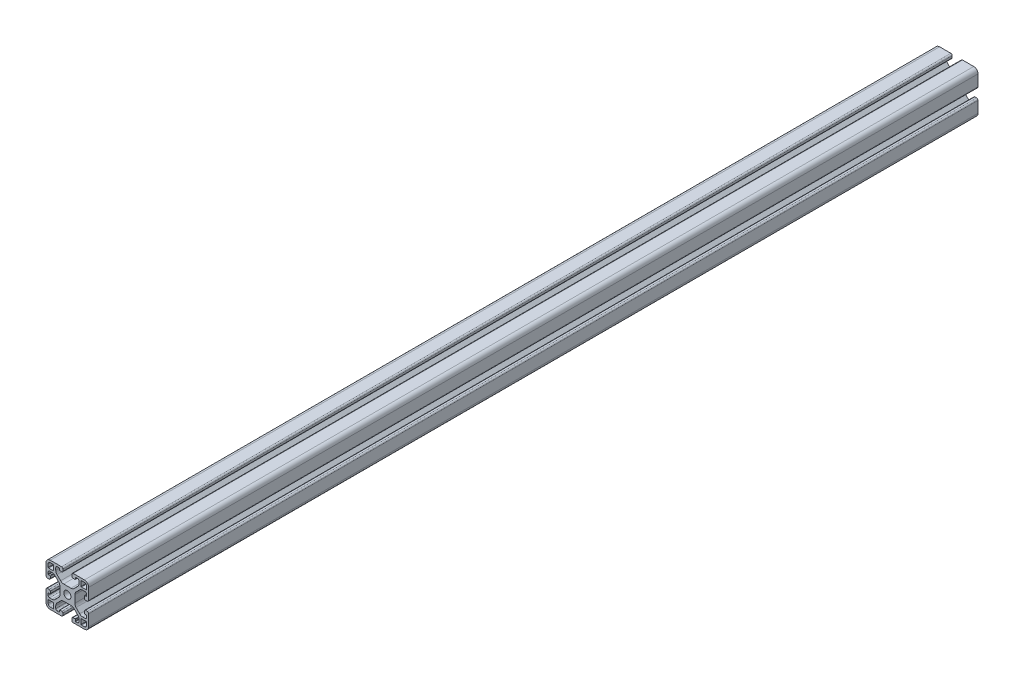
SolidWorks part; units mm, degrees
ref_plane "Plan de face" through (0, 0, 0) normal (0, 0, 1) x (1, 0, 0)
ref_plane "Plan de dessus" through (0, 0, 0) normal (0, 1, 0) x (1, 0, 0)
ref_plane "Plan de droite" through (0, 0, 0) normal (1, 0, 0) x (0, 0, -1)
ref_plane "Plan1" through (0, 0, 20) normal (0, 0, 1) x (1, 0, 0)
sketch "Esquisse1" plane through (0, 0, 20) normal (0, 0, 1) x (1, 0, 0)
  line L0 (20.3, 3) -> (18.9, 3)
  line L1 (18.1, 2.2) -> (18.1, 1)
  line L2 (19.1, 0) -> (27, 0)
  line L3 (30, 3) -> (30, 10.9)
  line L4 (29, 11.9) -> (27.8, 11.9)
  line L5 (27, 11.1) -> (27, 9.7)
  line L6 (27.3, 9.4) -> (28.2, 9.4)
  line L7 (28.5, 9.1) -> (28.5, 7.85)
  line L8 (27.5, 6.85) -> (25.8069, 6.85)
  line L9 (23.6855, 7.7287) -> (21.1287, 10.2855)
  line L10 (20.25, 12.4069) -> (20.25, 17.5931)
  line L11 (21.1287, 19.7145) -> (23.6855, 22.2713)
  line L12 (25.8069, 23.15) -> (27.5, 23.15)
  line L13 (28.5, 22.15) -> (28.5, 20.9)
  line L14 (28.2, 20.6) -> (27.3, 20.6)
  line L15 (27, 20.3) -> (27, 18.9)
  line L16 (27.8, 18.1) -> (29, 18.1)
  line L17 (30, 19.1) -> (30, 27)
  line L18 (27, 30) -> (19.1, 30)
  line L19 (18.1, 29) -> (18.1, 27.8)
  line L20 (18.9, 27) -> (20.3, 27)
  line L21 (20.6, 27.3) -> (20.6, 28.2)
  line L22 (20.9, 28.5) -> (22.15, 28.5)
  line L23 (23.15, 27.5) -> (23.15, 25.8069)
  line L24 (22.2713, 23.6855) -> (19.7145, 21.1287)
  line L25 (17.5931, 20.25) -> (12.4069, 20.25)
  line L26 (10.2855, 21.1287) -> (7.7287, 23.6855)
  line L27 (6.85, 25.8069) -> (6.85, 27.5)
  line L28 (7.85, 28.5) -> (9.1, 28.5)
  line L29 (9.4, 28.2) -> (9.4, 27.3)
  line L30 (9.7, 27) -> (11.1, 27)
  line L31 (11.9, 27.8) -> (11.9, 29)
  line L32 (10.9, 30) -> (3, 30)
  line L33 (0, 27) -> (0, 19.1)
  line L34 (1, 18.1) -> (2.2, 18.1)
  line L35 (3, 18.9) -> (3, 20.3)
  line L36 (2.7, 20.6) -> (1.8, 20.6)
  line L37 (1.5, 20.9) -> (1.5, 22.15)
  line L38 (2.5, 23.15) -> (4.1931, 23.15)
  line L39 (6.3145, 22.2713) -> (8.8713, 19.7145)
  line L40 (9.75, 17.5931) -> (9.75, 12.4069)
  line L41 (8.8713, 10.2855) -> (6.3145, 7.7287)
  line L42 (4.1931, 6.85) -> (2.5, 6.85)
  line L43 (1.5, 7.85) -> (1.5, 9.1)
  line L44 (1.8, 9.4) -> (2.7, 9.4)
  line L45 (3, 9.7) -> (3, 11.1)
  line L46 (2.2, 11.9) -> (1, 11.9)
  line L47 (0, 10.9) -> (0, 3)
  line L48 (3, 0) -> (10.9, 0)
  line L49 (11.9, 1) -> (11.9, 2.2)
  line L50 (11.1, 3) -> (9.7, 3)
  line L51 (9.4, 2.7) -> (9.4, 1.8)
  line L52 (9.1, 1.5) -> (7.85, 1.5)
  line L53 (6.85, 2.5) -> (6.85, 4.1931)
  line L54 (7.7287, 6.3145) -> (10.2855, 8.8713)
  line L55 (12.4069, 9.75) -> (17.5931, 9.75)
  line L56 (19.7145, 8.8713) -> (22.2713, 6.3145)
  line L57 (23.15, 4.1931) -> (23.15, 2.5)
  line L58 (22.15, 1.5) -> (20.9, 1.5)
  line L59 (20.6, 1.8) -> (20.6, 2.7)
  line L60 (5.35, 5.05) -> (5.35, 1.8)
  line L61 (5.05, 1.5) -> (3, 1.5)
  line L62 (1.5, 3) -> (1.5, 5.05)
  line L63 (1.8, 5.35) -> (5.05, 5.35)
  line L64 (24.95, 5.35) -> (28.2, 5.35)
  line L65 (28.5, 5.05) -> (28.5, 3)
  line L66 (27, 1.5) -> (24.95, 1.5)
  line L67 (24.65, 1.8) -> (24.65, 5.05)
  line L68 (24.65, 24.95) -> (24.65, 28.2)
  line L69 (24.95, 28.5) -> (27, 28.5)
  line L70 (28.5, 27) -> (28.5, 24.95)
  line L71 (28.2, 24.65) -> (24.95, 24.65)
  line L72 (5.05, 24.65) -> (1.8, 24.65)
  line L73 (1.5, 24.95) -> (1.5, 27)
  line L74 (3, 28.5) -> (5.05, 28.5)
  line L75 (5.35, 28.2) -> (5.35, 24.95)
  arc A0 (20.6, 2.7) -> (20.3, 3) centre (20.3, 2.7) ccw
  arc A1 (18.9, 3) -> (18.1, 2.2) centre (18.9, 2.2) ccw
  arc A2 (18.1, 1) -> (19.1, 0) centre (19.1, 1) ccw
  arc A3 (27, 0) -> (30, 3) centre (27, 3) ccw
  arc A4 (30, 10.9) -> (29, 11.9) centre (29, 10.9) ccw
  arc A5 (27.8, 11.9) -> (27, 11.1) centre (27.8, 11.1) ccw
  arc A6 (27, 9.7) -> (27.3, 9.4) centre (27.3, 9.7) ccw
  arc A7 (28.2, 9.4) -> (28.5, 9.1) centre (28.2, 9.1) cw
  arc A8 (28.5, 7.85) -> (27.5, 6.85) centre (27.5, 7.85) cw
  arc A9 (25.8069, 6.85) -> (23.6855, 7.7287) centre (25.8069, 9.85) cw
  arc A10 (21.1287, 10.2855) -> (20.25, 12.4069) centre (23.25, 12.4069) cw
  arc A11 (20.25, 17.5931) -> (21.1287, 19.7145) centre (23.25, 17.5931) cw
  arc A12 (23.6855, 22.2713) -> (25.8069, 23.15) centre (25.8069, 20.15) cw
  arc A13 (27.5, 23.15) -> (28.5, 22.15) centre (27.5, 22.15) cw
  arc A14 (28.5, 20.9) -> (28.2, 20.6) centre (28.2, 20.9) cw
  arc A15 (27.3, 20.6) -> (27, 20.3) centre (27.3, 20.3) ccw
  arc A16 (27, 18.9) -> (27.8, 18.1) centre (27.8, 18.9) ccw
  arc A17 (29, 18.1) -> (30, 19.1) centre (29, 19.1) ccw
  arc A18 (30, 27) -> (27, 30) centre (27, 27) ccw
  arc A19 (19.1, 30) -> (18.1, 29) centre (19.1, 29) ccw
  arc A20 (18.1, 27.8) -> (18.9, 27) centre (18.9, 27.8) ccw
  arc A21 (20.3, 27) -> (20.6, 27.3) centre (20.3, 27.3) ccw
  arc A22 (20.6, 28.2) -> (20.9, 28.5) centre (20.9, 28.2) cw
  arc A23 (22.15, 28.5) -> (23.15, 27.5) centre (22.15, 27.5) cw
  arc A24 (23.15, 25.8069) -> (22.2713, 23.6855) centre (20.15, 25.8069) cw
  arc A25 (19.7145, 21.1287) -> (17.5931, 20.25) centre (17.5931, 23.25) cw
  arc A26 (12.4069, 20.25) -> (10.2855, 21.1287) centre (12.4069, 23.25) cw
  arc A27 (7.7287, 23.6855) -> (6.85, 25.8069) centre (9.85, 25.8069) cw
  arc A28 (6.85, 27.5) -> (7.85, 28.5) centre (7.85, 27.5) cw
  arc A29 (9.1, 28.5) -> (9.4, 28.2) centre (9.1, 28.2) cw
  arc A30 (9.4, 27.3) -> (9.7, 27) centre (9.7, 27.3) ccw
  arc A31 (11.1, 27) -> (11.9, 27.8) centre (11.1, 27.8) ccw
  arc A32 (11.9, 29) -> (10.9, 30) centre (10.9, 29) ccw
  arc A33 (3, 30) -> (0, 27) centre (3, 27) ccw
  arc A34 (0, 19.1) -> (1, 18.1) centre (1, 19.1) ccw
  arc A35 (2.2, 18.1) -> (3, 18.9) centre (2.2, 18.9) ccw
  arc A36 (3, 20.3) -> (2.7, 20.6) centre (2.7, 20.3) ccw
  arc A37 (1.8, 20.6) -> (1.5, 20.9) centre (1.8, 20.9) cw
  arc A38 (1.5, 22.15) -> (2.5, 23.15) centre (2.5, 22.15) cw
  arc A39 (4.1931, 23.15) -> (6.3145, 22.2713) centre (4.1931, 20.15) cw
  arc A40 (8.8713, 19.7145) -> (9.75, 17.5931) centre (6.75, 17.5931) cw
  arc A41 (9.75, 12.4069) -> (8.8713, 10.2855) centre (6.75, 12.4069) cw
  arc A42 (6.3145, 7.7287) -> (4.1931, 6.85) centre (4.1931, 9.85) cw
  arc A43 (2.5, 6.85) -> (1.5, 7.85) centre (2.5, 7.85) cw
  arc A44 (1.5, 9.1) -> (1.8, 9.4) centre (1.8, 9.1) cw
  arc A45 (2.7, 9.4) -> (3, 9.7) centre (2.7, 9.7) ccw
  arc A46 (3, 11.1) -> (2.2, 11.9) centre (2.2, 11.1) ccw
  arc A47 (1, 11.9) -> (0, 10.9) centre (1, 10.9) ccw
  arc A48 (0, 3) -> (3, 0) centre (3, 3) ccw
  arc A49 (10.9, 0) -> (11.9, 1) centre (10.9, 1) ccw
  arc A50 (11.9, 2.2) -> (11.1, 3) centre (11.1, 2.2) ccw
  arc A51 (9.7, 3) -> (9.4, 2.7) centre (9.7, 2.7) ccw
  arc A52 (9.4, 1.8) -> (9.1, 1.5) centre (9.1, 1.8) cw
  arc A53 (7.85, 1.5) -> (6.85, 2.5) centre (7.85, 2.5) cw
  arc A54 (6.85, 4.1931) -> (7.7287, 6.3145) centre (9.85, 4.1931) cw
  arc A55 (10.2855, 8.8713) -> (12.4069, 9.75) centre (12.4069, 6.75) cw
  arc A56 (17.5931, 9.75) -> (19.7145, 8.8713) centre (17.5931, 6.75) cw
  arc A57 (22.2713, 6.3145) -> (23.15, 4.1931) centre (20.15, 4.1931) cw
  arc A58 (23.15, 2.5) -> (22.15, 1.5) centre (22.15, 2.5) cw
  arc A59 (20.9, 1.5) -> (20.6, 1.8) centre (20.9, 1.8) cw
  circle A60 centre (15, 15) radius 2.5
  arc A61 (5.05, 5.35) -> (5.35, 5.05) centre (5.05, 5.05) cw
  arc A62 (5.35, 1.8) -> (5.05, 1.5) centre (5.05, 1.8) cw
  arc A63 (3, 1.5) -> (1.5, 3) centre (3, 3) cw
  arc A64 (1.5, 5.05) -> (1.8, 5.35) centre (1.8, 5.05) cw
  arc A65 (24.65, 5.05) -> (24.95, 5.35) centre (24.95, 5.05) cw
  arc A66 (28.2, 5.35) -> (28.5, 5.05) centre (28.2, 5.05) cw
  arc A67 (28.5, 3) -> (27, 1.5) centre (27, 3) cw
  arc A68 (24.95, 1.5) -> (24.65, 1.8) centre (24.95, 1.8) cw
  arc A69 (24.95, 24.65) -> (24.65, 24.95) centre (24.95, 24.95) cw
  arc A70 (24.65, 28.2) -> (24.95, 28.5) centre (24.95, 28.2) cw
  arc A71 (27, 28.5) -> (28.5, 27) centre (27, 27) cw
  arc A72 (28.5, 24.95) -> (28.2, 24.65) centre (28.2, 24.95) cw
  arc A73 (5.35, 24.95) -> (5.05, 24.65) centre (5.05, 24.95) cw
  arc A74 (1.8, 24.65) -> (1.5, 24.95) centre (1.8, 24.95) cw
  arc A75 (1.5, 27) -> (3, 28.5) centre (3, 27) cw
  arc A76 (5.05, 28.5) -> (5.35, 28.2) centre (5.05, 28.2) cw
extrude "Boss.-Extru.1" add sketch "Esquisse1" against normal blind 625
